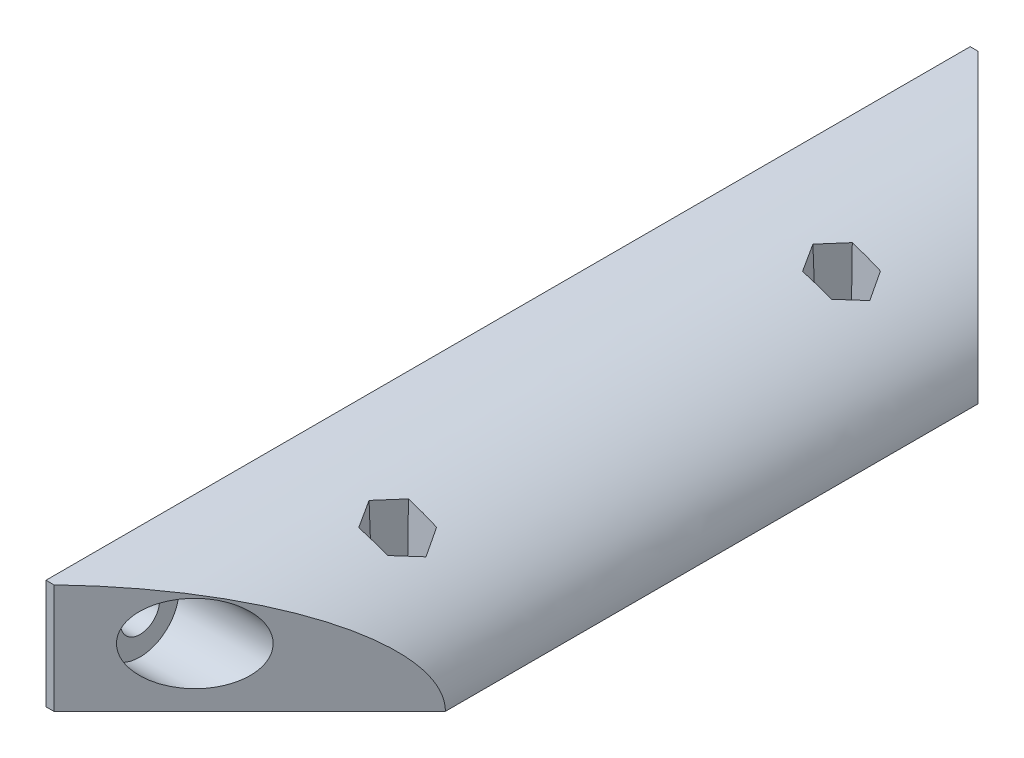
SolidWorks part; units mm, degrees
material "ABS"
ref_plane "Plan de face" through (0, 0, 0) normal (0, 0, 1) x (1, 0, 0)
ref_plane "Plan de dessus" through (0, 0, 0) normal (0, 1, 0) x (1, 0, 0)
ref_plane "Plan de droite" through (0, 0, 0) normal (1, 0, 0) x (0, 0, -1)
sketch "Esquisse1" plane through (0, 0, 0) normal (0, 0, 1) x (1, 0, 0)
  line L0 (0, 15.5) -> (0, 0)
  line L1 (0, 0) -> (27.5, 0)
  dimension "D1" = 15.5
  dimension "D2" = 27.5
extrude "Extru.-Mince1" add sketch "Esquisse1" along normal blind 118 thin thin type one direction reverse wall 1.5
sketch "Esquisse2" plane through (0, 0, 0) normal (-1, 0, 0) x (0, 0, 1)
  line L0 (59, 15.5) -> (59, 0) construction
  line L1 (118, 15.5) -> (0, 15.5) construction
  line L2 (118, 0) -> (0, 0) construction
  line L3 (0, 15.5) -> (0, 0) construction
  circle A0 centre (9, 9) radius 2.5
  circle A1 centre (109, 9) radius 2.5
  dimension "D1" = 100
  dimension "D2" = 5
  dimension "D3" = 9
  dimension "D4" = 9
  dimension "D5" = 6.5
extrude "Enlèv. mat.-Extru.1" cut sketch "Esquisse2" against normal blind 4
sketch "Esquisse3" plane through (0, 0, 0) normal (0, -1, 0) x (1, 0, 0)
  line L0 (27.5, 59) -> (-130, 59) construction
  line L1 (27.5, 118) -> (27.5, 0) construction
  line L2 (-130, 59) -> (15.7716, 30.6649) construction
  line L3 (0, 118) -> (0, 0) construction
  circle A1 centre (15.7716, 30.6649) radius 1.5
  circle A2 centre (15.7716, 87.3351) radius 1.5
  dimension "D1" = 11
  dimension "D3" = 3
  dimension "D2" = 148.5
  dimension "D5" = 130
extrude "Enlèv. mat.-Extru.2" cut sketch "Esquisse3" against normal blind 4
chamfer "Chanfrein1" distance 25 angle 45 2 edges at (27.5, 0.75, 118) (27.5, 0.75, 0)
sketch "Esquisse4" plane through (0, 0, 0) normal (0, 0, -1) x (-1, 0, 0)
  line L0 (-27.5, 1.5) -> (-1.5, 1.5)
  line L1 (-1.5, 1.5) -> (-1.5, 15.5)
  ellipse E0 centre (-1.5, 1.5) end of major axis (-27.5, 1.5) minor radius 14 (-1.5, 15.5) -> (-27.5, 1.5) ccw
extrude "Boss.-Extru.1" add sketch "Esquisse4" against normal up to surface (118 mm away) separate body up to face at (1.3333, 5.6667, 118)
sketch "Esquisse5" plane through (1.5, 0, 0) normal (-1, 0, 0) x (0, 0, 1)
  circle A0 centre (109, 9) radius 2.5 construction
  circle A1 centre (9, 9) radius 2.5 construction
  circle A2 centre (109, 9) radius 2.5
  circle A3 centre (9, 9) radius 2.5
extrude "Enlèv. mat.-Extru.3" cut sketch "Esquisse5" against normal through all
sketch "Esquisse6" plane through (0, 0, 0) normal (0, -1, 0) x (1, 0, 0)
  line L0 (27.5, 93) -> (2.5, 118) construction
  line L1 (2.5, 0) -> (27.5, 25) construction
  line L2 (27.5, 93) -> (2.5, 118)
  line L3 (2.5, 0) -> (27.5, 25)
  line L4 (27.5, 118) -> (1.5, 118)
  line L5 (1.5, 118) -> (1.5, 0)
  line L6 (1.5, 0) -> (27.5, 0)
  line L7 (27.5, 0) -> (27.5, 118)
  line L8 (27.5, 118) -> (2.5, 118)
  line L9 (27.5, 93) -> (27.5, 118)
  line L10 (2.5, 0) -> (27.5, 0)
  line L11 (27.5, 0) -> (27.5, 25)
  circle A0 centre (15.7716, 87.3351) radius 1.5 construction
  circle A1 centre (15.7716, 30.6649) radius 1.5 construction
  circle A2 centre (15.7716, 87.3351) radius 1.5
  circle A3 centre (15.7716, 30.6649) radius 1.5
  dimension "D1" = 0
extrude "Enlèv. mat.-Extru.4" cut sketch "Esquisse6" against normal through all
delete or keep bodies "Corps-Effacer/suppr1" type delete bodies bodies 104
sketch "Esquisse8" plane through (1.5, 0, 0) normal (-1, 0, 0) x (0, 0, 1)
  circle A0 centre (9, 9) radius 5
  circle A1 centre (109, 9) radius 5
  dimension "D1" = 10
extrude "Enlèv. mat.-Extru.5" cut sketch "Esquisse8" against normal through all from offset 3 offset against normal yes
sketch "Esquisse9" plane through (0, 1.5, 0) normal (0, -1, 0) x (1, 0, 0)
  line L1 (19.0625, 87.3351) -> (17.4171, 90.1851)
  line L2 (17.4171, 90.1851) -> (14.1262, 90.1851)
  line L3 (14.1262, 90.1851) -> (12.4807, 87.3351)
  line L4 (12.4807, 87.3351) -> (14.1262, 84.4851)
  line L5 (14.1262, 84.4851) -> (17.4171, 84.4851)
  line L6 (17.4171, 84.4851) -> (19.0625, 87.3351)
  line L7 (17.4171, 33.5149) -> (14.1262, 33.5149)
  line L8 (14.1262, 33.5149) -> (12.4807, 30.6649)
  line L9 (12.4807, 30.6649) -> (14.1262, 27.8149)
  line L10 (14.1262, 27.8149) -> (17.4171, 27.8149)
  line L11 (17.4171, 27.8149) -> (19.0625, 30.6649)
  line L12 (19.0625, 30.6649) -> (17.4171, 33.5149)
  circle A0 centre (15.7716, 87.3351) radius 2.85 construction
  circle A1 centre (15.7716, 30.6649) radius 2.85 construction
  dimension "D1" = 5.7
extrude "Enlèv. mat.-Extru.6" cut sketch "Esquisse9" against normal through all draft 2 from offset 3
